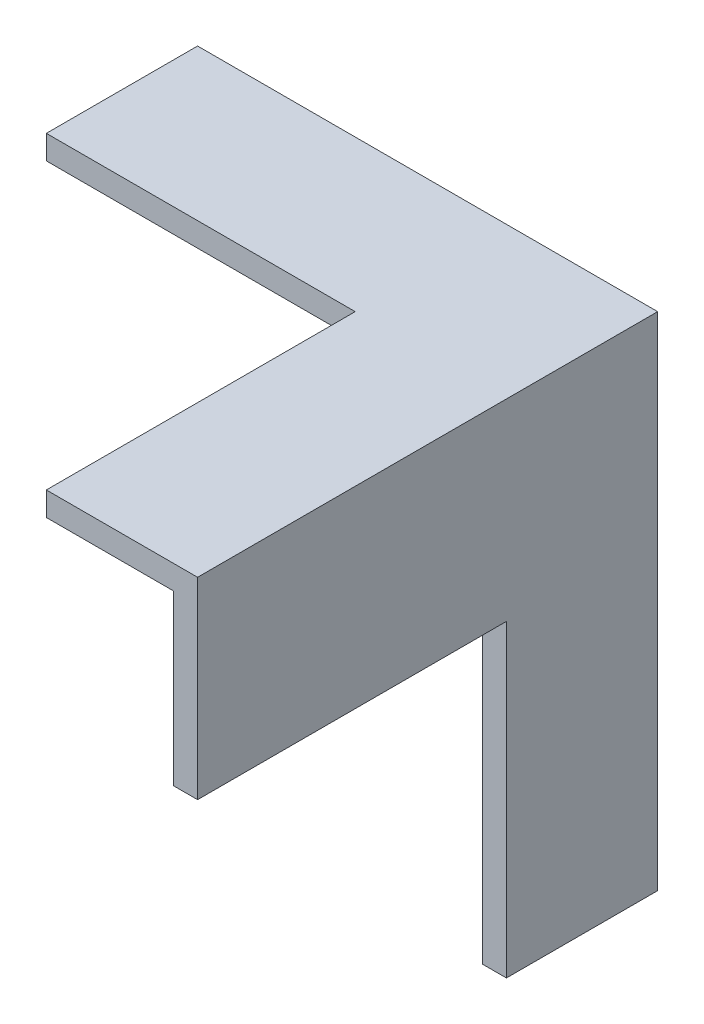
SolidWorks part; units mm, degrees
ref_plane "Front Plane" through (0, 0, 0) normal (0, 0, 1) x (1, 0, 0)
ref_plane "Top Plane" through (0, 0, 0) normal (0, 1, 0) x (1, 0, 0)
ref_plane "Right Plane" through (0, 0, 0) normal (1, 0, 0) x (0, 0, -1)
sketch "Sketch2" plane through (0, 0, 0) normal (1, 0, 0) x (0, 0, -1)
  line L0 (0, 0) -> (73.406, 0)
  line L1 (73.406, 0) -> (73.406, -76.2)
  line L2 (73.406, -76.2) -> (49.276, -76.2)
  line L3 (49.276, -76.2) -> (49.276, -26.924)
  line L4 (49.276, -26.924) -> (0, -26.924)
  line L5 (0, -26.924) -> (0, 0)
  dimension "D1" = 73.406
  dimension "D2" = 76.2
  dimension "D3" = 49.276
  dimension "D4" = 24.13
extrude "Boss-Extrude1" add sketch "Sketch2" along normal blind 3.81
sketch "Sketch5" plane through (0, 0, 0) normal (0, 1, 0) x (1, 0, 0)
  line L0 (-69.596, 73.406) -> (3.81, 73.406)
  line L2 (-69.596, 73.406) -> (-69.596, 49.276)
  line L3 (-69.596, 49.276) -> (-20.32, 49.276)
  line L4 (-20.32, 49.276) -> (-20.32, 0)
  line L5 (-20.32, 0) -> (3.81, 0)
  line L6 (3.81, 0) -> (3.81, 73.406)
  dimension "D1" = 24.13
  dimension "D2" = 49.276
  dimension "D3" = 73.406
extrude "Boss-Extrude2" add sketch "Sketch5" along normal blind 3.81
sketch "Sketch6" plane through (0, 3.81, 0) normal (0, 1, 0) x (1, 0, 0)
  point P0 (-55.2671, 60.6835)
  point P1 (-34.6898, 60.6835)
  point P2 (-8.3137, 13.5779)
  point P3 (-8.3137, 32.5796)
